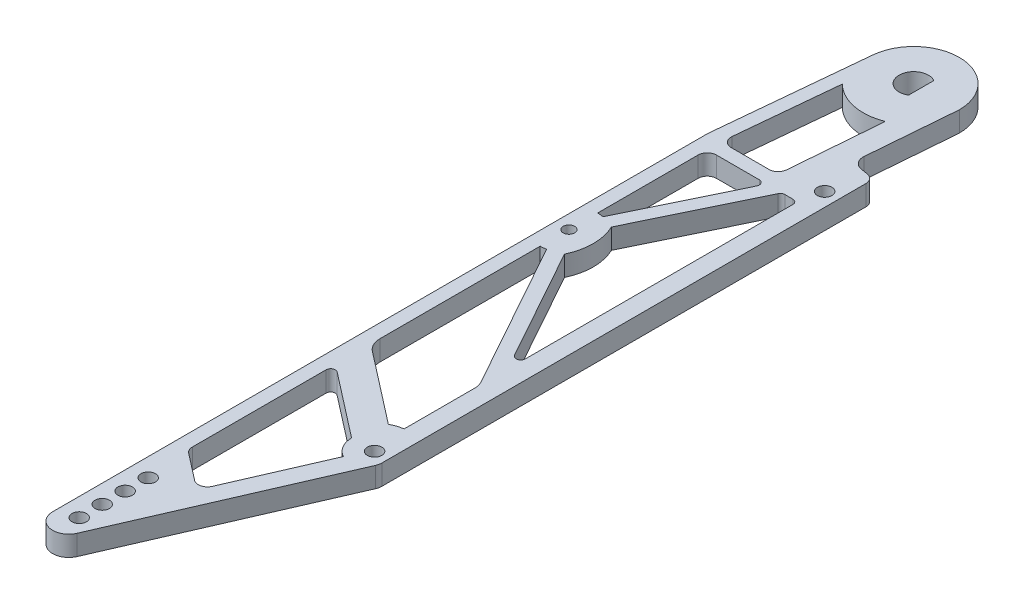
SolidWorks part; units mm, degrees
material "6061-T6 (SS)"
ref_plane "X-Y Datum" through (0, 0, 0) normal (0, 0, 1) x (1, 0, 0)
ref_plane "X-Z Datum" through (0, 0, 0) normal (0, 1, 0) x (1, 0, 0)
ref_plane "Y-Z Datum" through (0, 0, 0) normal (1, 0, 0) x (0, 0, -1)
other "Graphic1" [suppressed]
other "Graphic (Closed) -1" [suppressed]
sketch "Sketch2" plane through (0, 0, 0) normal (0, 1, 0) x (1, 0, 0)
  line L5 (13.4859, -162.4108) -> (-11.43, -143.082) construction
  line L8 (0, 0) -> (0, -24.13) construction
  line L11 (15.1556, -28.0184) -> (13.2387, -27.713)
  line L15 (-16.51, -221.3289) -> (-16.51, -40.4661)
  line L22 (-7.9887, -223.1013) -> (16.9799, -165.6775)
  line L23 (17.2959, -164.1583) -> (17.2959, -30.5268)
  line L33 (10.4385, -167.9818) -> (-0.5342, -193.2173)
  line L44 (-7.4473, -76.0744) -> (7.5755, -45.0536)
  line L45 (8.7185, -44.3372) -> (10.9459, -44.3372)
  line L46 (12.2159, -45.6072) -> (12.2159, -119.4928)
  line L47 (9.8359, -120.11) -> (-7.4473, -89.0256)
  line L49 (-12.4315, -37.7433) -> (-9.7554, -9.9996)
  line L51 (5.1277, -12.9949) -> (3.0693, -38.194)
  line L53 (0.5377, -40.5272) -> (-9.9032, -40.5272)
  line L56 (1.663, -44.3372) -> (-10.16, -44.3372)
  line L57 (13.7382, -24.5776) -> (0, 0) construction
  line L58 (10.5738, -24.3191) -> (12.5603, 0)
  line L59 (-12.7, -149.6154) -> (-12.7, -186.5441)
  line L63 (7.1359, -162.4108) -> (-10.6516, -148.612)
  line L64 (-12.7, -74.6125) -> (-12.7, -46.8772)
  line L65 (2.8061, -46.1607) -> (-11.056, -74.7846)
  line L66 (-16.4983, -40.2222) -> (-12.5023, 1.2059)
  line L67 (-4.4204, -194.2114) -> (-11.7169, -188.551)
  line L68 (5.8058, -44.3372) -> (-12.7, -82.55) construction
  line L69 (-1.7326, -64.2739) -> (-5.1616, -62.6133) construction
  line L70 (8.9236, -154.0495) -> (-10.7338, -138.8001)
  line L71 (12.2159, -152.9708) -> (12.2159, -133.548)
  line L72 (11.5758, -131.0794) -> (-11.086, -90.3217)
  line L75 (-12.7, -134.7862) -> (-12.7, -90.4875)
  line L76 (2.05, -3.4928) -> (2.05, 3.4928)
  circle A0 centre (0, 0) radius 4.05
  circle A2 centre (-11.43, -219.075) radius 2
  circle A3 centre (-11.43, -212.725) radius 2
  circle A4 centre (-11.43, -206.375) radius 2
  circle A5 centre (-11.43, -200.025) radius 2
  circle A7 centre (0, 0) radius 12.5603 construction
  circle A8 centre (-12.7, -82.55) radius 1.5875
  circle A12 centre (13.4859, -38.1) radius 2
  arc A13 (-12.5023, 1.2059) -> (12.5603, 0) centre (0, 0) cw
  arc A14 (-7.4473, -89.0256) -> (-7.4473, -76.0744) centre (-20.962, -82.55) ccw
  circle A16 centre (24.0125, -14.7036) radius 3.175 construction
  arc A17 (24.0125, -14.7036) -> (13.7382, -24.5776) centre (0, 0) cw construction
  circle A18 centre (13.7382, -24.5776) radius 3.175 construction
  arc A19 (13.2387, -27.713) -> (10.5738, -24.3191) centre (13.7382, -24.5776) cw
  arc A20 (15.1556, -28.0184) -> (17.2959, -30.5268) centre (14.7559, -30.5268) cw
  circle A21 centre (13.4859, -162.4108) radius 2
  arc A24 (10.4385, -167.9818) -> (7.1359, -162.4108) centre (13.4859, -162.4108) cw
  arc A25 (-16.51, -221.3289) -> (-7.9887, -223.1013) centre (-12.065, -221.3289) ccw
  arc A26 (-12.7, -74.6125) -> (-11.056, -74.7846) centre (-12.7, -82.55) cw
  arc A28 (5.1277, -12.9949) -> (-9.7554, -9.9996) centre (0, 0) cw
  arc A31 (-10.16, -44.3372) -> (-12.7, -46.8772) centre (-10.16, -46.8772) ccw
  arc A32 (-12.4315, -37.7433) -> (-9.9032, -40.5272) centre (-9.9032, -37.9872) ccw
  arc A33 (0.5377, -40.5272) -> (3.0693, -38.194) centre (0.5377, -37.9872) ccw
  arc A36 (-12.7, -149.6154) -> (-10.6516, -148.612) centre (-11.43, -149.6154) cw
  arc A37 (9.8359, -120.11) -> (12.2159, -119.4928) centre (10.9459, -119.4928) ccw
  arc A38 (7.5755, -45.0536) -> (8.7185, -44.3372) centre (8.7185, -45.6072) cw
  arc A39 (10.9459, -44.3372) -> (12.2159, -45.6072) centre (10.9459, -45.6072) cw
  arc A40 (1.663, -44.3372) -> (2.8061, -46.1607) centre (1.663, -45.6072) cw
  arc A50 (17.2959, -164.1583) -> (16.9799, -165.6775) centre (13.4859, -164.1583) cw
  arc A52 (-16.4983, -40.2222) -> (-16.51, -40.4661) centre (-13.97, -40.4661) ccw
  arc A53 (-12.7, -186.5441) -> (-11.7169, -188.551) centre (-10.16, -186.5441) ccw
  arc A54 (-4.4204, -194.2114) -> (-0.5342, -193.2173) centre (-2.8635, -192.2045) ccw
  arc A55 (12.2159, -152.9708) -> (8.9236, -154.0495) centre (13.4859, -162.4108) ccw
  arc A56 (-11.086, -90.3217) -> (-12.7, -90.4875) centre (-12.7, -82.55) cw
  arc A57 (-12.7, -134.7862) -> (-10.7338, -138.8001) centre (-7.62, -134.7862) ccw
  arc A58 (11.5758, -131.0794) -> (12.2159, -133.548) centre (7.1359, -133.548) cw
  point P30 (17.2959, -28.3595)
  point P44 (-3.4471, -63.4436)
  point P45 (-1.8376, -196.215)
  point P48 (12.2159, -82.55)
  point P75 (-4.05, 0)
  point P88 (-12.7, -44.3372)
  point P91 (-12.7, -40.5272)
  point P104 (12.2159, -124.3904)
  point P107 (7.9224, -44.3372)
  point P110 (12.2159, -44.3372)
  point P120 (17.2959, -164.9508)
  dimension "D1" = 8.1
  dimension "D6" = 4
  dimension "D12" = 24.13
  dimension "D5" = 25.1206
  dimension "D14" = 3.175
  dimension "D19" = 4
  dimension "D20" = 6.35
  dimension "D24" = 3.81
  dimension "D50" = 14.986
  dimension "D51" = 8.262
  dimension "D42" = 3.81
  dimension "D62" = 6.35
  dimension "D63" = 29.204
  dimension "D27" = 2.54
  dimension "D44" = 4
  dimension "D18" = 4.445
  dimension "D34" = 3.81
  dimension "D36" = 6.35
  dimension "D33" = 13.97
  dimension "D38" = 3.81
  dimension "D39" = 8.89
  dimension "D48" = 2.54
  dimension "D49" = 1.27
  dimension "D52" = 3.81
  dimension "D53" = 3.81
  dimension "D54" = 9.525
  dimension "D58" = 2.54
  dimension "D59" = 3.81
  dimension "D64" = 6.1
  dimension "D29" = 7.9375
  dimension "D31" = 3.81
  dimension "D41" = 2.54
  dimension "D55" = 7.9375
  dimension "D57" = 5.08
  dimension "D7" = 6.35
  dimension "D8" = 6.35
  dimension "D9" = 6.35
  dimension "D10" = 5.08
  dimension "D11" = 5.08
  dimension "D13" = 4.1084
  dimension "D15" = 82.55
  dimension "D16" = 12.7
  dimension "D17" = 13.7382
  dimension "D21" = 136.5913
  dimension "D22" = 38.1
  dimension "D23" = 13.4859
  dimension "D25" = 5.08
  dimension "D26" = 3.81
  dimension "D28" = 40.5272
  dimension "D30" = 2.54
  dimension "D32" = 3.81
  dimension "D35" = 3.81
  dimension "D37" = 16.51
  dimension "D40" = 23.5
  dimension "D43" = 200.025
  dimension "D45" = 6.35
  dimension "D46" = 6.35
  dimension "D47" = 4.2935
  dimension "D56" = 3.81
  dimension "D60" = 24.0125
  dimension "D61" = 14.7036
extrude "Boss-Extrude1" add sketch "Sketch2" along normal blind 5.588 contours L66 A52 L15 A25 L22 A50 L23 A20 L11 A19 L58 A13 A54 L67 A53 L59 A36 L63 A24 L33 L56 A40 L65 A26 L64 A31 L45 A39 L46 A37 L47 A14 L44 A38 A0 A2 A3 A4 A5 A8 | L76 A0
sketch "Sketch6" plane through (-16.51, 0, 0) normal (-1, 0, 0) x (0, 0, 1)
  line L0 (183.2289, 5.588) -> (183.2289, 0)
  line L3 (221.3289, 5.588) -> (221.3289, 0) construction
  line L4 (221.3289, 5.588) -> (40.4661, 5.588) construction
  line L5 (221.3289, 0) -> (40.4661, 0) construction
  dimension "D1" = 38.1
split line "Split Line2"
sketch "Sketch7" plane through (0, 0, 0) normal (0, -1, 0) x (1, 0, 0)
  line L0 (0, 0) -> (0, 23.7661) construction
